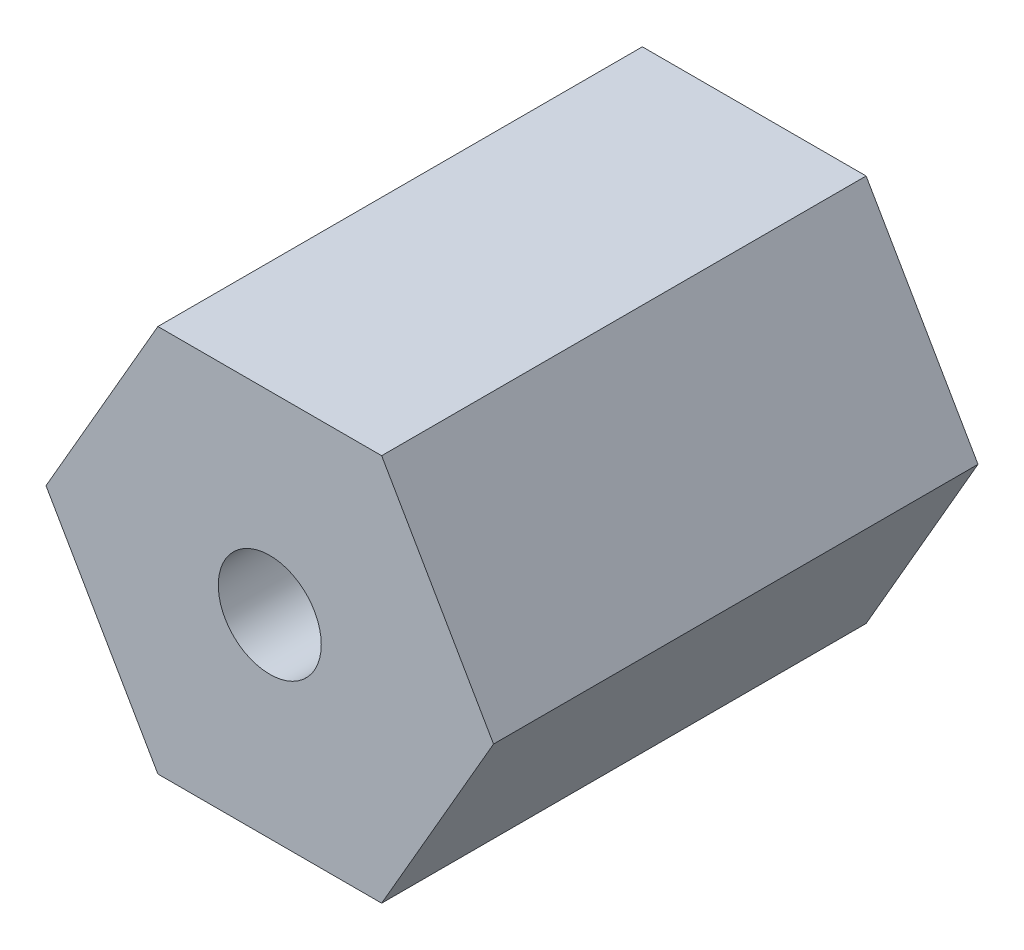
SolidWorks part; units mm, degrees
ref_plane "Front Plane" through (0, 0, 0) normal (0, 0, 1) x (1, 0, 0)
ref_plane "Top Plane" through (0, 0, 0) normal (0, 1, 0) x (1, 0, 0)
ref_plane "Right Plane" through (0, 0, 0) normal (1, 0, 0) x (0, 0, -1)
sketch "Sketch1" plane through (0, 0, 0) normal (0, 0, 1) x (1, 0, 0)
  line L1 (-5.8659, 0) -> (-2.9329, -5.08)
  line L2 (-2.9329, -5.08) -> (2.9329, -5.08)
  line L3 (2.9329, -5.08) -> (5.8659, 0)
  line L4 (5.8659, 0) -> (2.9329, 5.08)
  line L5 (2.9329, 5.08) -> (-2.9329, 5.08)
  line L6 (-2.9329, 5.08) -> (-5.8659, 0)
  circle A0 centre (0, 0) radius 5.08 construction
  circle A1 centre (0, 0) radius 5.08
  dimension "D2" = 10.16
extrude "Boss-Extrude1" add sketch "Sketch1" along normal blind 12.7 contours A1 | A1 L5 L6 | A1 L4 L5 | A1 L3 L4 | A1 L2 L3 | A1 L6 L1 | A1 L1 L2
hole_wizard "M3x0.5 Tapped Hole1" positions "Sketch2" profile "Sketch3" tap size "M3x0.5" standard "ANSI Metric" end condition through all
sketch "Sketch2" plane through (0, 0, 12.7) normal (0, 0, 1) x (1, 0, 0)
  point P0 (0, 0)
sketch "Sketch3" plane through (0, 0, 12.7) normal (1, 0, 0) x (0, -1, 0)
  line L0 (0, 0) -> (0, 12.7)
  line L1 (0, 12.7) -> (1.35, 12.7)
  line L2 (1.35, 12.7) -> (1.35, 0)
  line L5 (1.35, 0) -> (0, 0)
  line L11 (0, -6.35) -> (0, 107.95) construction
  dimension "Thread Major Dia." = 2.7
  dimension "Thru Tap Drill Depth" = 12.7
